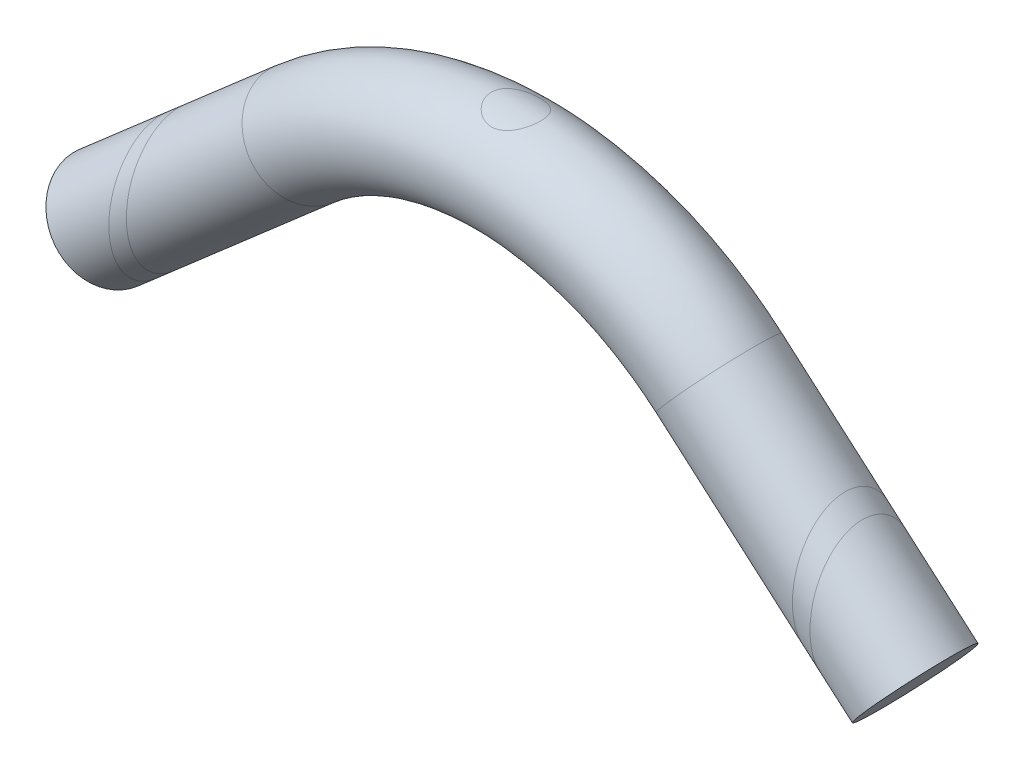
SolidWorks part; units mm, degrees
ref_plane "Front Plane" through (0, 0, 0) normal (0, 0, 1) x (1, 0, 0)
ref_plane "Top Plane" through (0, 0, 0) normal (0, 1, 0) x (1, 0, 0)
ref_plane "Right Plane" through (0, 0, 0) normal (1, 0, 0) x (0, 0, -1)
sketch "Sketch1" plane through (0, 0, 0) normal (0, 0, 1) x (1, 0, 0)
  line L0 (0, 0) -> (230, 0) construction
  line L1 (115, 0) -> (115, 70) construction
  line L2 (115, 70) -> (115, 100) construction
  line L3 (0, 0) -> (55.9439, 48.6469)
  line L4 (230, 0) -> (174.0561, 48.6469)
  arc A0 (174.0561, 48.6469) -> (55.9439, 48.6469) centre (115, -19.2676) ccw
  point P9 (115, 70.7324)
  dimension "D2" = 70
  dimension "D4" = 90
  dimension "D1" = 230
  dimension "D3" = 30
ref_plane "Plane1" through (115, 0, 0) normal (1, 0, 0) x (0, 0, -1)
ref_plane "Plane2" through (15, 0, 0) normal (1, 0, 0) x (0, 0, -1)
ref_plane "Plane4" through (210, 0, 0) normal (1, 0, 0) x (0, 0, -1)
ref_plane "Plane3" through (215, 0, 0) normal (1, 0, 0) x (0, 0, -1)
ref_plane "Plane5" through (20, 0, 0) normal (1, 0, 0) x (0, 0, -1)
sketch "Sketch3" plane through (115, 0, 0) normal (1, 0, 0) x (0, 0, -1)
  circle A0 centre (0, 70.7324) radius 15
sweep "Sweep1" add profiles "Sketch3" path "Sketch1"
mirror "Mirror1" about plane through (115, 0, 0) normal (1, 0, 0) of "Sweep1"
sketch "Sketch6" plane through (115, 0, 0) normal (1, 0, 0) x (0, 0, -1)
  line L0 (0, 176.1177) -> (0, 0.3524)
  line L1 (0, 0.3524) -> (-47.0962, 176.1177)
  dimension "D1" = 15
sketch "Sketch4" plane through (0, 0, 0) normal (0, 1, 0) x (1, 0, 0)
  circle A0 centre (116.1146, 0) radius 7
split line "Split Line4"
split line "Split Line2"
split line "Split Line3"
split line "Split Line5"
split line "Split Line6"
sketch "Sketch5" plane through (0, 0, 0) normal (0, 0, 1) x (1, 0, 0)
  line L0 (0, 0) -> (232.0005, 0) construction
ref_plane "Plane6" through (0, 0, 0) normal (0, -0.2588, 0.9659) x (1, 0, 0)
